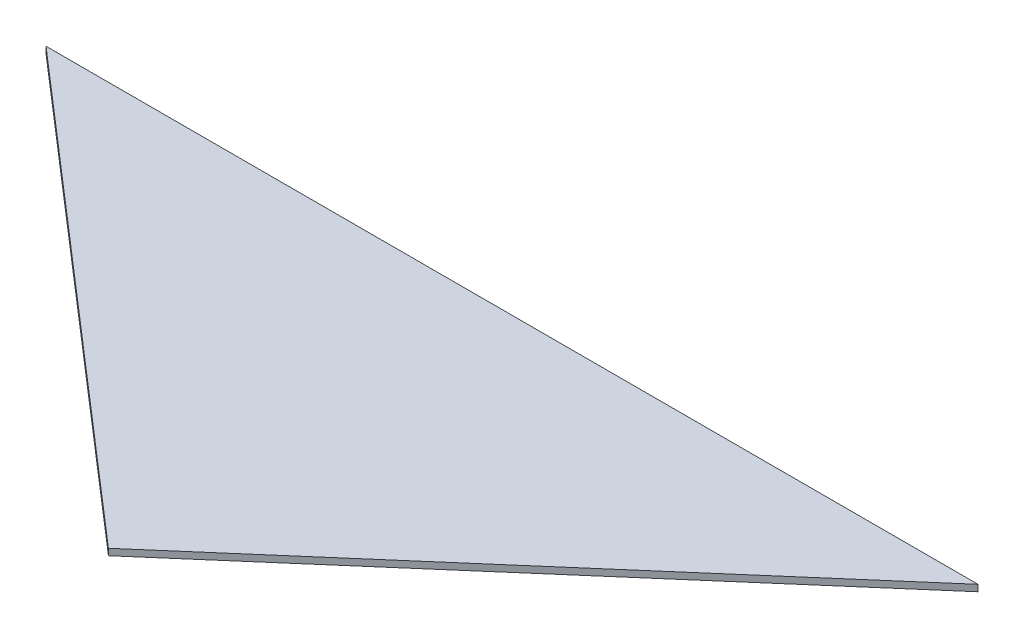
SolidWorks part; units mm, degrees
ref_plane "Front Plane" through (0, 0, 0) normal (0, 0, 1) x (1, 0, 0)
ref_plane "Top Plane" through (0, 0, 0) normal (0, 1, 0) x (1, 0, 0)
ref_plane "Right Plane" through (0, 0, 0) normal (1, 0, 0) x (0, 0, -1)
sketch "Sketch1" plane through (0, 0, 0) normal (0, 1, 0) x (1, 0, 0)
  line L0 (-457.2, 0) -> (457.2, 0)
  line L1 (457.2, 0) -> (228.6, 395.9468) construction
  line L2 (228.6, 395.9468) -> (-228.6, 395.9468) construction
  line L3 (-228.6, 395.9468) -> (-457.2, 0) construction
  line L4 (-457.2, 0) -> (-228.6, -395.9468) construction
  line L5 (-228.6, -395.9468) -> (228.6, -395.9468) construction
  line L6 (228.6, -395.9468) -> (457.2, 0) construction
  line L7 (0, 0) -> (0, -395.9468)
  line L8 (0, -395.9468) -> (457.2, 0)
  line L9 (0, -395.9468) -> (-457.2, 0)
  circle A0 centre (0, 0) radius 395.9468 construction
  dimension "D1" = 914.4
extrude "Boss-Extrude2" add sketch "Sketch1" along normal blind 6.35 contours L9 L7 L0 | L7 L8 L0
